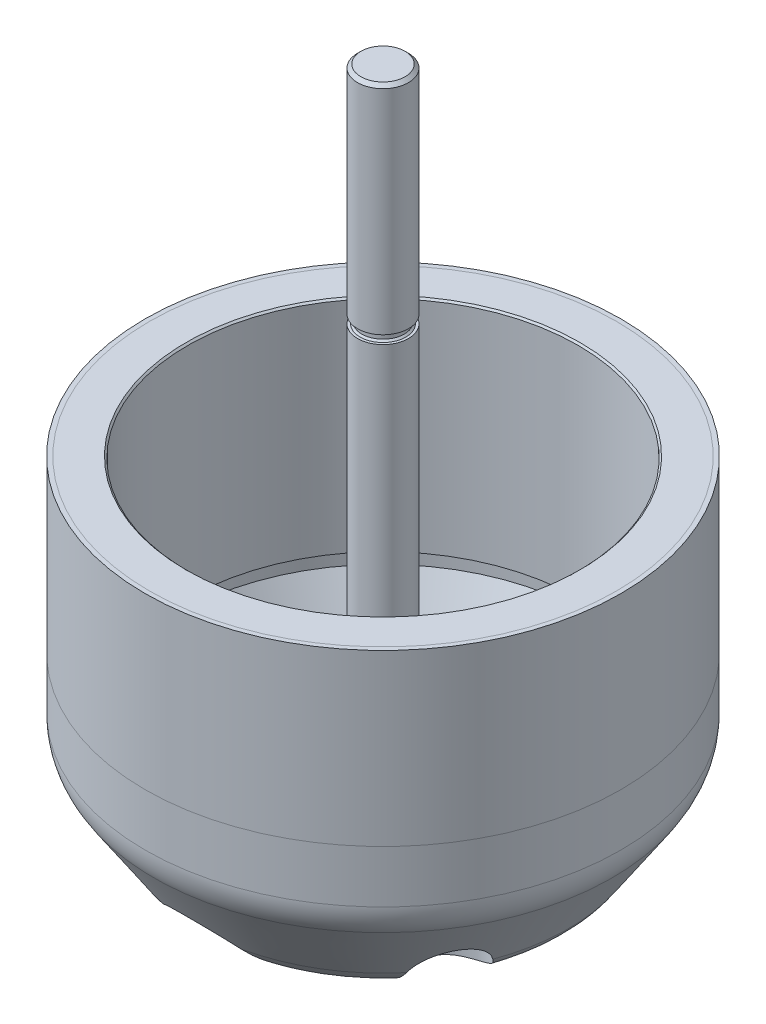
SolidWorks part; units mm, degrees
ref_plane "Front Plane" through (0, 0, 0) normal (0, 0, 1) x (1, 0, 0)
ref_plane "Top Plane" through (0, 0, 0) normal (0, 1, 0) x (1, 0, 0)
ref_plane "Right Plane" through (0, 0, 0) normal (1, 0, 0) x (0, 0, -1)
sketch "Sketch1" plane through (0, 0, 0) normal (0, 0, 1) x (1, 0, 0)
  line L0 (4.5, 0) -> (8.3944, 0)
  line L1 (14, 6.9083) -> (14, 10)
  line L2 (13.75, 20) -> (11.6, 20)
  line L3 (12, 7) -> (12, 6)
  line L4 (13.75, 20) -> (13.75, 10)
  line L5 (14, 10) -> (13.75, 10)
  line L6 (10.8906, 1.3359) -> (13.4962, 5.2442)
  line L7 (4.5, 2) -> (8.1459, 2)
  line L8 (4.5, 0) -> (4.5, -1.9)
  line L9 (1.6, -2) -> (4.4, -2)
  line L10 (1.5, -1.9) -> (1.5, 4.4)
  line L11 (10.8292, 3.6584) -> (12, 6)
  line L12 (4.4, -2) -> (4.5, -1.9)
  line L13 (1.6, -2) -> (1.5, -1.9)
  line L14 (1.5, 4.4) -> (1.6, 4.5)
  line L15 (12, 6) -> (11.9963, 6.0107)
  line L16 (0, -5) -> (0, 30) construction
  line L17 (1.6, 4.5) -> (3.4783, 4.5)
  line L18 (4.5, 2) -> (3.4783, 4.5)
  line L19 (12, 7) -> (11.5, 7)
  line L20 (11.5, 7) -> (11.5, 19.9)
  line L21 (11.5, 19.9) -> (11.6, 20)
  arc A1 (10.8292, 3.6584) -> (8.1459, 2) centre (8.1459, 5) cw
  arc A2 (10.8906, 1.3359) -> (8.3944, 0) centre (8.3944, 3) cw
  arc A3 (13.4962, 5.2442) -> (14, 6.9083) centre (11, 6.9083) ccw
  point P0 (1.5, -2)
  point P14 (1.5, 2)
  point P17 (4.5, -2)
  point P29 (1.5, 4.5)
  point P35 (11.5, 20)
revolve "Revolve1" add sketch "Sketch1" angle 360 about L16
sketch "Sketch2" plane through (0, 0, 0) normal (0, -1, 0) x (1, 0, 0)
  line L0 (20, 0) -> (0, 0) construction
  line L1 (0, 0) -> (0, 20.0145) construction
  line L2 (0, 0) -> (23.3636, 13.489) construction
  circle A0 centre (0, 8) radius 3.5
  circle A2 centre (0, 0) radius 4.5 construction
  circle A3 centre (5.1962, 3) radius 1
  circle A4 centre (8.6603, 5) radius 2
  circle A5 centre (6.9282, -4) radius 3.5
  circle A6 centre (0, -10) radius 2
  circle A7 centre (0, -6) radius 1
  circle A8 centre (-6.9282, -4) radius 3.5
  circle A9 centre (-8.6603, 5) radius 2
  circle A10 centre (-5.1962, 3) radius 1
  point P28 (0, 0)
  point P46 (0, 0)
  dimension "D1" = 7
  dimension "D2" = 2
  dimension "D3" = 60
  dimension "D4" = 4
  dimension "D5" = 6
  dimension "D6" = 10
extrude "Cut-Extrude1" cut sketch "Sketch2" against normal blind 3.5
sketch "Sketch3" plane through (0, 0, 0) normal (0, 0, 1) x (1, 0, 0)
  line L0 (13.75, 10) -> (13.75, 20) construction
  line L1 (13.75, 10) -> (13.75, 20)
  line L2 (13.75, 20) -> (14.01, 20)
  line L3 (14.01, 20) -> (14.01, 10)
  line L4 (14.01, 10) -> (13.75, 10)
  line L5 (0, -4) -> (0, 27.25) construction
  dimension "D1" = 0.26
revolve "Revolve2" add sketch "Sketch3" angle 360 about L5
sketch "Sketch4" plane through (0, -2, 0) normal (0, -1, 0) x (1, 0, 0)
  circle A0 centre (0, 0) radius 1.5
extrude "Boss-Extrude1" add sketch "Sketch4" against normal blind 42 separate body
chamfer "Chamfer1" distance 0.2 angle 45 2 edges at (0, -2, -1.5) (0, 40, -1.5)
sketch "Sketch5" plane through (0, 0, 0) normal (0, 0, 1) x (1, 0, 0)
  line L13 (0, 43) -> (0, 25.25) construction
  line L14 (1.5, 27.25) -> (1.35, 27.25)
  line L15 (1.25, 27.15) -> (1.25, 26.85)
  line L16 (1.35, 26.75) -> (1.5, 26.75)
  line L17 (1.5, 26.75) -> (1.5, 27.25)
  line L18 (1.35, 27.25) -> (1.25, 27.15)
  line L19 (1.25, 26.85) -> (1.35, 26.75)
  point P22 (1.25, 27.25)
  point P24 (1.25, 26.75)
  dimension "D7" = 0.1
  dimension "D8" = 0.1
  dimension "D9" = 0.1
  dimension "D11" = 0.1
revolve "Cut-Revolve1" cut sketch "Sketch5" angle 360 about L13
